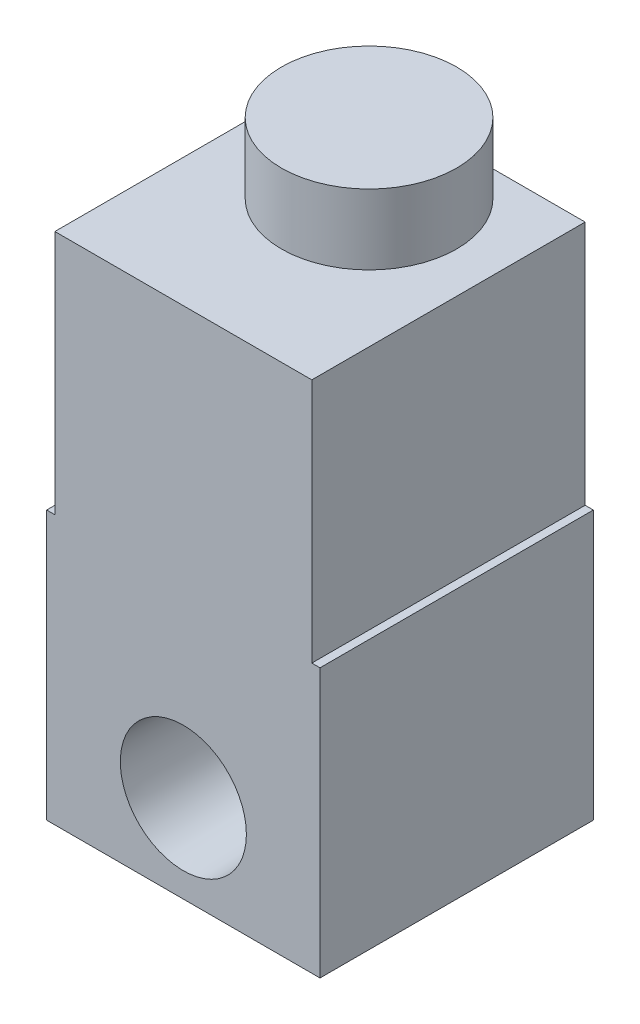
SolidWorks part; units mm, degrees
ref_plane "Front Plane" through (0, 0, 0) normal (0, 0, 1) x (1, 0, 0)
ref_plane "Top Plane" through (0, 0, 0) normal (0, 1, 0) x (1, 0, 0)
ref_plane "Right Plane" through (0, 0, 0) normal (1, 0, 0) x (0, 0, -1)
sketch "Sketch1" plane through (0, 0, 0) normal (0, 0, 1) x (1, 0, 0)
  line L0 (0, 38.6349) -> (0, -37.2746) construction
  line L1 (-67.3043, 0) -> (74.7199, 0) construction
  line L2 (0, 0) -> (0, 29.21)
  line L3 (0, 29.21) -> (0.889, 29.21)
  line L4 (0.889, 29.21) -> (0.889, 55.88)
  line L5 (0.889, 55.88) -> (28.829, 55.88)
  line L6 (28.829, 55.88) -> (28.829, 29.21)
  line L7 (28.829, 29.21) -> (29.718, 29.21)
  line L8 (29.718, 29.21) -> (29.718, 0)
  line L9 (29.718, 0) -> (0, 0)
  point P8 (0, 0)
  dimension "D1" = 27.94
  dimension "D2" = 29.718
  dimension "D3" = 55.88
  dimension "D4" = 29.21
extrude "Boss-Extrude1" add sketch "Sketch1" along normal blind 29.718
sketch "Sketch3" plane through (0, 55.88, 0) normal (0, 1, 0) x (1, 0, 0)
  line L0 (14.859, 0) -> (14.859, -29.718) construction
  line L1 (28.829, 0) -> (0.889, 0) construction
  line L2 (28.829, -29.718) -> (0.889, -29.718) construction
  circle A0 centre (14.859, -9.525) radius 9.525
  point P2 (0, 0)
  dimension "D1" = 19.05
extrude "Boss-Extrude2" add sketch "Sketch3" along normal blind 7.62
sketch "Sketch6" plane through (0, 0, 29.718) normal (0, 0, 1) x (1, 0, 0)
  line L0 (0, 0) -> (29.718, 0) construction
  line L1 (0, 0) -> (29.718, 0)
  line L2 (14.859, 21.1279) -> (14.859, -10.5877) construction
  point P4 (14.859, 9.525)
  point P7 (0, 0)
  dimension "D1" = 9.525
sketch "Sketch11" plane through (0, 0, 29.718) normal (0, 0, 1) x (1, 0, 0)
  point P0 (14.859, 9.525)
hole_wizard "1/4 NPT Tapped Hole1" positions "Sketch11" profile "Sketch13" size "1/4" standard "ANSI Inch" end condition through all
sketch "Sketch13" plane through (14.859, 9.525, 29.718) normal (1, 0, 0) x (0, -1, 0)
  line L0 (0, 0) -> (0, 29.718)
  line L1 (0, 29.718) -> (6.1976, 29.718)
  line L2 (6.1976, 29.718) -> (5.5626, 29.083)
  line L3 (5.5626, 29.083) -> (5.5626, 9.906)
  line L4 (5.5626, 9.906) -> (6.558, 9.906)
  line L5 (6.558, 9.906) -> (6.8546, 0)
  line L6 (-6.558, 9.906) -> (-6.8546, 0) construction
  line L7 (6.8546, 0) -> (0, 0)
  line L8 (0, -6.35) -> (0, 107.95) construction
  line L10 (-6.1976, 29.718) -> (-5.5626, 29.083) construction
  line L11 (-5.5626, 9.906) -> (-6.558, 9.906) construction
  dimension "Thru Tap Drill Dia." = 11.1252
  dimension "Thru Tap Drill Depth" = 29.718
  dimension "Thread Dia." = 13.7092
  dimension "Thread Angle" = 3.43
  dimension "Thread Depth" = 9.906
  dimension "Far C'Sink Dia." = 12.3952
  dimension "Far C'Sink Angle" = 90
